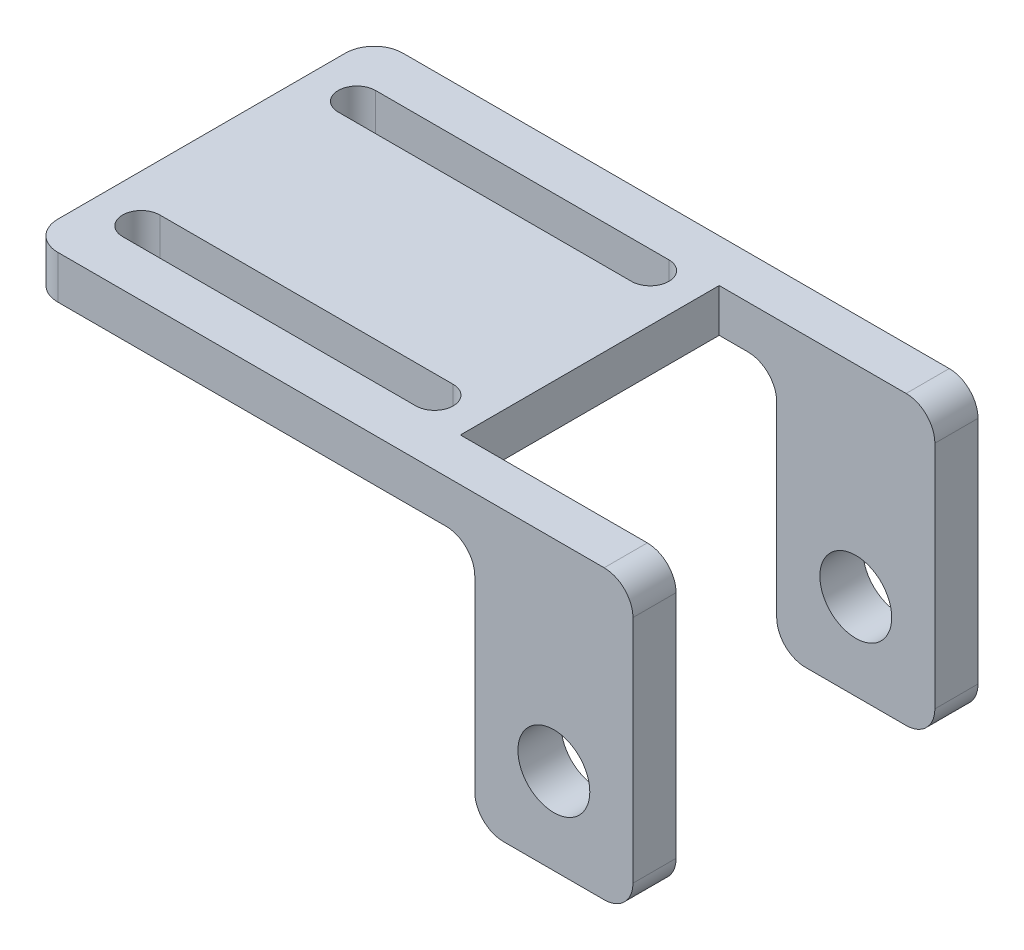
SolidWorks part; units mm, degrees
ref_plane "Front Plane" through (0, 0, 0) normal (0, 0, 1) x (1, 0, 0)
ref_plane "Top Plane" through (0, 0, 0) normal (0, 1, 0) x (1, 0, 0)
ref_plane "Right Plane" through (0, 0, 0) normal (1, 0, 0) x (0, 0, -1)
sketch "Sketch1" plane through (0, 0, 0) normal (0, 1, 0) x (1, 0, 0)
  line L1 (0, 0) -> (42, 0)
  line L2 (0, 0) -> (0, 24)
  line L3 (0, 24) -> (42, 24)
  line L4 (42, 0) -> (42, 24)
  dimension "D1" = 24
  dimension "D2" = 42
extrude "Boss-Extrude1" add sketch "Sketch1" along normal blind 3
sketch "Sketch2" plane through (0, 0, 0) normal (0, -1, 0) x (1, 0, 0)
  line L1 (42, 0) -> (31, 0)
  line L2 (42, 0) -> (42, -3)
  line L3 (42, -3) -> (31, -3)
  line L4 (31, 0) -> (31, -3)
  line L5 (42, -24) -> (31, -24)
  line L6 (42, -24) -> (42, -21)
  line L7 (42, -21) -> (31, -21)
  line L8 (31, -24) -> (31, -21)
  dimension "D1" = 3
  dimension "D2" = 3
  dimension "D3" = 11
  dimension "D4" = 11
extrude "Boss-Extrude2" add sketch "Sketch2" along normal blind 17
sketch "Sketch3" plane through (0, 0, 0) normal (0, 0, 1) x (1, 0, 0)
  line L0 (0, 3) -> (42, 3) construction
  line L4 (36.5, 3) -> (36.5, -17) construction
  line L5 (42, -17) -> (31, -17) construction
  circle A0 centre (36.5, -11) radius 2.5
  point P0 (36.5, -6)
  dimension "D1" = 5
  dimension "D2" = 6
extrude "Cut-Extrude1" cut sketch "Sketch3" against normal through all
sketch "Sketch4" plane through (0, 3, 0) normal (0, 1, 0) x (1, 0, 0)
  line L0 (42, 0) -> (42, 24) construction
  line L1 (42, 21) -> (27, 21)
  line L2 (42, 21) -> (42, 3)
  line L3 (42, 3) -> (27, 3)
  line L4 (27, 21) -> (27, 3)
  line L5 (42, 24) -> (0, 24) construction
  line L6 (0, 0) -> (42, 0) construction
  dimension "D1" = 3
  dimension "D2" = 3
  dimension "D3" = 15
extrude "Cut-Extrude2" cut sketch "Sketch4" against normal blind 3
fillet "Fillet1" radius 2 2 edges at (0, 1.5, -24) (0, 1.5, 0)
fillet "Fillet2" radius 2 6 edges at (42, 3, -1.5) (42, -17, -1.5) (31, -17, -1.5) (42, -17, -22.5) (31, -17, -22.5) (42, 3, -22.5)
fillet "Fillet3" radius 2 2 edges at (31, 0, -1.5) (31, 0, -22.5)
sketch "Sketch6" plane through (0, 3, 0) normal (0, 1, 0) x (1, 0, 0)
  line L0 (27, 19.5) -> (0, 19.5) construction
  line L1 (27, 21) -> (27, 3) construction
  line L2 (0, 22) -> (0, 2) construction
  line L3 (27, 4.5) -> (0, 4.5) construction
  line L4 (3.3, 19.5) -> (23.7, 19.5) construction
  line L5 (3.3, 20.8) -> (23.7, 20.8)
  line L6 (3.3, 18.2) -> (23.7, 18.2)
  line L7 (3.3, 4.5) -> (23.7, 4.5) construction
  line L8 (3.3, 5.8) -> (23.7, 5.8)
  line L9 (3.3, 3.2) -> (23.7, 3.2)
  line L10 (0, 12) -> (27, 12) construction
  arc A0 (3.3, 20.8) -> (3.3, 18.2) centre (3.3, 19.5) ccw
  arc A1 (23.7, 18.2) -> (23.7, 20.8) centre (23.7, 19.5) ccw
  arc A2 (3.3, 5.8) -> (3.3, 3.2) centre (3.3, 4.5) ccw
  arc A3 (23.7, 3.2) -> (23.7, 5.8) centre (23.7, 4.5) ccw
  point P12 (13.5, 19.5)
  point P17 (13.5, 4.5)
  point P24 (25, 4.5)
  point P25 (25, 19.5)
  point P26 (2, 4.5)
  point P27 (2, 19.5)
  dimension "D1" = 1.5
  dimension "D2" = 1.5
  dimension "D3" = 2.6
  dimension "D4" = 2.6
  dimension "D5" = 2
  dimension "D6" = 2
  dimension "D7" = 2
  dimension "D8" = 2
  dimension "D9" = 7.5
extrude "Cut-Extrude3" cut sketch "Sketch6" against normal through all
sketch "Sketch5" plane through (0, 3, 0) normal (0, 1, 0) x (1, 0, 0)
  line L0 (0, 12) -> (27, 12) construction
  line L1 (0, 22) -> (0, 2) construction
  line L2 (27, 21) -> (27, 3) construction
sketch "Sketch7" plane through (0, 0, 0) normal (0, -1, 0) x (1, 0, 0)
  line L0 (0, -12) -> (27, -12) construction
